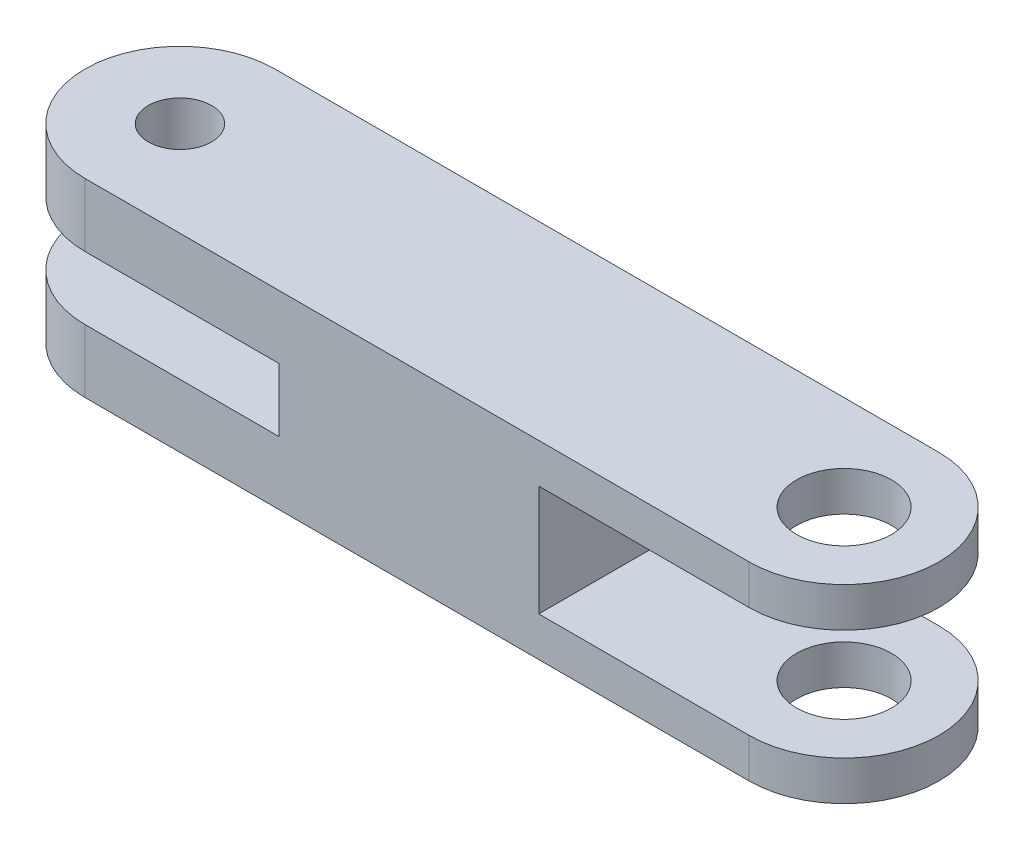
SolidWorks part; units mm, degrees
ref_plane "前视基准面" through (0, 0, 0) normal (0, 0, 1) x (1, 0, 0)
ref_plane "上视基准面" through (0, 0, 0) normal (0, 1, 0) x (1, 0, 0)
ref_plane "右视基准面" through (0, 0, 0) normal (1, 0, 0) x (0, 0, -1)
other "Configuration Table"
sketch "草图1" plane through (0, 0, 0) normal (0, 1, 0) x (1, 0, 0)
  line L0 (0, 0) -> (1, 0) construction
  line L1 (19.5, 0) -> (21, 0) construction
  line L2 (0, 3) -> (21, 3)
  line L3 (0, -3) -> (21, -3)
  arc A0 (0, 3) -> (0, -3) centre (0, 0) ccw
  arc A1 (21, -3) -> (21, 3) centre (21, 0) ccw
  circle A2 centre (21, 0) radius 1.5
  circle A3 centre (0, 0) radius 1
  point P3 (20, 0)
  dimension "D2" = 3
  dimension "D3" = 3
  dimension "D4" = 2
  dimension "D1" = 21
extrude "凸台-拉伸1" add sketch "草图1" along normal mid plane 6
sketch "草图6" plane through (0, 0, 0) normal (0, 1, 0) x (1, 0, 0)
  line L0 (14.3461, 7.8432) -> (14.3461, -3.762)
  line L1 (14.3461, -3.762) -> (45.8575, -3.762)
  line L2 (45.8575, -3.762) -> (45.8575, 7.8432)
  line L3 (45.8575, 7.8432) -> (14.3461, 7.8432)
extrude "切除-拉伸2" cut sketch "草图6" against normal mid plane 3.5
sketch "草图7" plane through (0, 0, 0) normal (0, 1, 0) x (1, 0, 0)
  line L0 (6.139, 5.0358) -> (6.139, -4.6141)
  line L1 (6.139, -4.6141) -> (-6.5212, -4.6141)
  line L2 (-6.5212, -4.6141) -> (-6.5212, 5.0358)
  line L3 (-6.5212, 5.0358) -> (6.139, 5.0358)
extrude "切除-拉伸3" cut sketch "草图7" against normal mid plane 2
